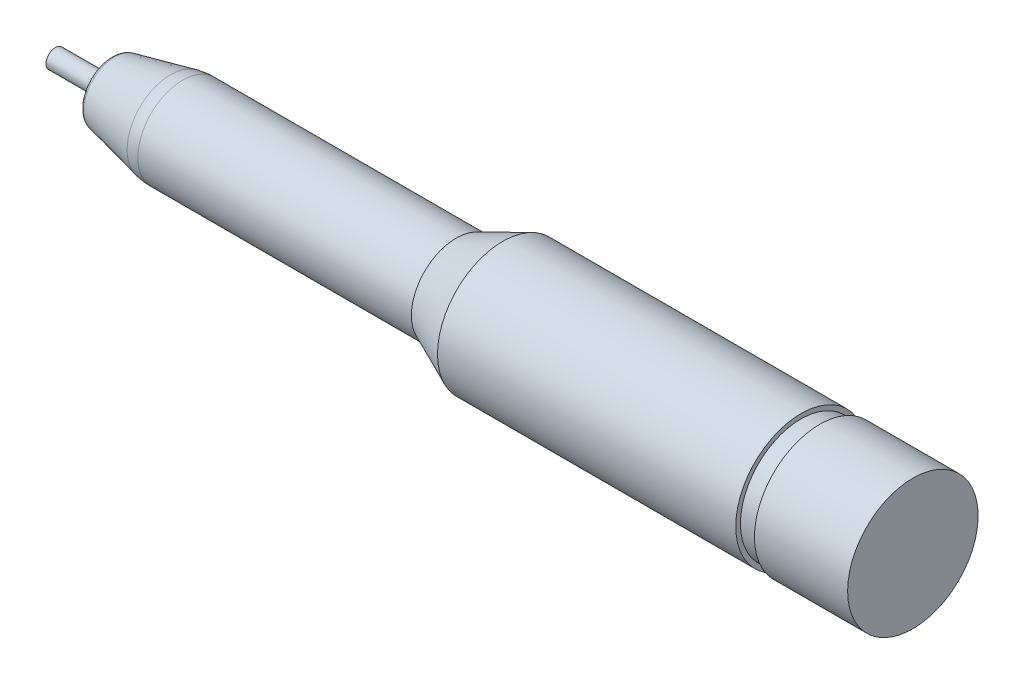
SolidWorks part; units mm, degrees
ref_plane "Plano frontal" through (0, 0, 0) normal (0, 0, 1) x (1, 0, 0)
ref_plane "Plano superior" through (0, 0, 0) normal (0, 1, 0) x (1, 0, 0)
ref_plane "Plano direito" through (0, 0, 0) normal (1, 0, 0) x (0, 0, -1)
sketch "Esboço1" plane through (0, 0, 0) normal (0, 0, 1) x (1, 0, 0)
  line L0 (0, 0) -> (92, 0)
  line L1 (92, 0) -> (92, 7)
  line L2 (92, 7) -> (82, 7)
  line L3 (82, 7) -> (82, 6.5)
  line L4 (82, 6.5) -> (80, 6.5)
  line L5 (80, 7) -> (80, 6.5)
  line L6 (80, 7) -> (48, 7)
  line L7 (48, 7) -> (43, 4.8)
  line L8 (43, 4.8) -> (13, 4.8)
  line L9 (13, 4.8) -> (6, 3.25)
  line L10 (6, 3.25) -> (6, 1)
  line L11 (6, 1) -> (0, 1)
  line L12 (0, 1) -> (0, 0)
  dimension "D1" = 1
  dimension "D2" = 6
  dimension "D3" = 3.25
  dimension "D4" = 7
  dimension "D5" = 4.8
  dimension "D6" = 92
  dimension "D7" = 10
  dimension "D8" = 2
  dimension "D9" = 34
  dimension "D10" = 2
  dimension "D11" = 5
  dimension "D12" = 7
  dimension "D13" = 0.5
  dimension "D14" = 7
  dimension "D16" = 92
revolve "Revolução1" add sketch "Esboço1" angle 360 about L0
cosmetic thread "Representação de rosca1" parameters "D1"=5, "D2"=11.797
fillet "Filete2" radius 0.5 1 edges at (6, 0, 3.25)
fillet "Filete4" radius 6 1 edges at (13, 0, 4.8)
